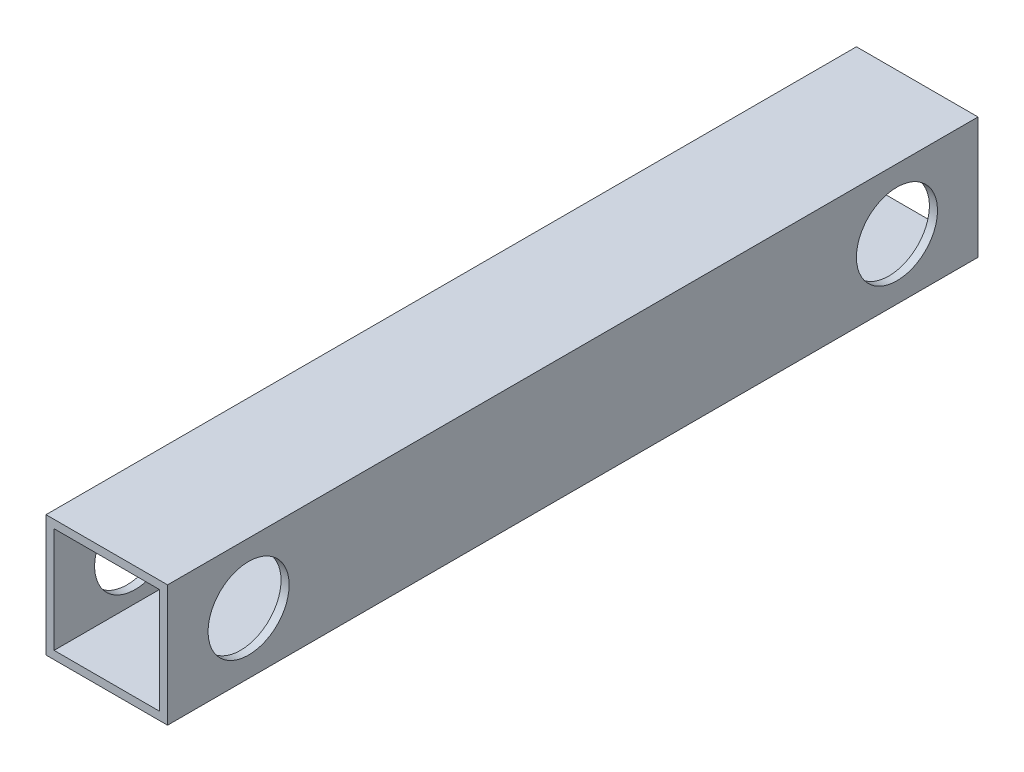
SolidWorks part; units mm, degrees
ref_plane "Front Plane" through (0, 0, 0) normal (0, 0, 1) x (1, 0, 0)
ref_plane "Top Plane" through (0, 0, 0) normal (0, 1, 0) x (1, 0, 0)
ref_plane "Right Plane" through (0, 0, 0) normal (1, 0, 0) x (0, 0, -1)
sketch "Sketch1" plane through (0, 0, 0) normal (0, 0, 1) x (1, 0, 0)
  line L1 (-15, -15) -> (15, -15)
  line L2 (-15, -15) -> (-15, 15)
  line L3 (-15, 15) -> (15, 15)
  line L4 (15, -15) -> (15, 15)
  line L5 (-15, -15) -> (15, 15) construction
  line L6 (-15, 15) -> (15, -15) construction
  line L7 (-13, -13) -> (13, -13)
  line L8 (-13, -13) -> (-13, 13)
  line L9 (-13, 13) -> (13, 13)
  line L10 (13, -13) -> (13, 13)
  line L11 (-13, -13) -> (13, 13) construction
  line L12 (-13, 13) -> (13, -13) construction
  point P0 (0, 0)
  point P6 (0, 0)
  dimension "D1" = 30
  dimension "D2" = 30
  dimension "D3" = 2
  dimension "D4" = 2
extrude "Boss-Extrude1" add sketch "Sketch1" along normal blind 200
sketch "Sketch2" plane through (15, 0, 0) normal (1, 0, 0) x (0, 0, -1)
  line L0 (-200, 0) -> (0, 0) construction
  line L1 (-200, -15) -> (-200, 15) construction
  line L2 (-100, 15) -> (-100, -15) construction
  line L3 (-200, 15) -> (0, 15) construction
  line L4 (-200, -15) -> (0, -15) construction
  circle A0 centre (-180, 0) radius 10
  circle A1 centre (-20, 0) radius 10
  dimension "D1" = 20
  dimension "D2" = 20
extrude "Cut-Extrude1" cut sketch "Sketch2" against normal blind 200
